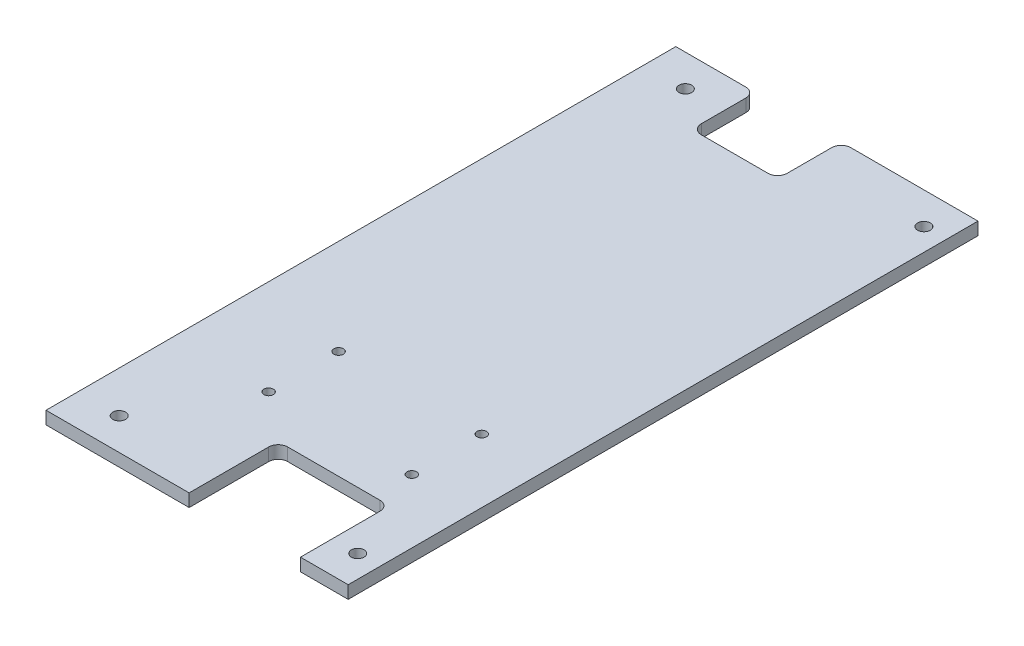
SolidWorks part; units mm, degrees
ref_plane "前视基准面" through (0, 0, 0) normal (0, 0, 1) x (1, 0, 0)
ref_plane "上视基准面" through (0, 0, 0) normal (0, 1, 0) x (1, 0, 0)
ref_plane "右视基准面" through (0, 0, 0) normal (1, 0, 0) x (0, 0, -1)
sketch "草图1" plane through (0, 0, 0) normal (0, 1, 0) x (1, 0, 0)
  line L1 (47.5, -99) -> (-47.5, -99)
  line L2 (47.5, -99) -> (47.5, 99)
  line L3 (47.5, 99) -> (-47.5, 99)
  line L4 (-47.5, -99) -> (-47.5, 99)
  line L5 (47.5, -99) -> (-47.5, 99) construction
  line L6 (47.5, 99) -> (-47.5, -99) construction
  point P0 (0, 0)
  dimension "D1" = 198
  dimension "D2" = 95
extrude "凸台-拉伸1" add sketch "草图1" along normal blind 4
sketch "草图2" plane through (0, 4, 0) normal (0, 1, 0) x (1, 0, 0)
  line L0 (32.5, -99) -> (32.5, -71)
  line L1 (-47.5, -99) -> (47.5, -99) construction
  line L2 (32.5, -71) -> (-2.5, -71)
  line L3 (-2.5, -71) -> (-2.5, -99)
  line L4 (47.5, -99) -> (47.5, 99) construction
  line L5 (-2.5, -99) -> (32.5, -99)
  dimension "D1" = 35
  dimension "D2" = 15
  dimension "D3" = 28
extrude "切除-拉伸1" cut sketch "草图2" against normal blind 4
sketch "草图3" plane through (0, 4, 0) normal (0, 1, 0) x (1, 0, 0)
  line L0 (32.5, -99) -> (32.5, -71) construction
  line L1 (32.5, -99) -> (47.5, -99) construction
  circle A0 centre (40.5, -89) radius 2
  dimension "D1" = 8
  dimension "D2" = 10
  dimension "D3" = 4
extrude "切除-拉伸2" cut sketch "草图3" against normal through all
sketch "草图4" plane through (0, 4, 0) normal (0, 1, 0) x (1, 0, 0)
  line L0 (47.5, 99) -> (-47.5, 99) construction
  line L1 (32.5, -99) -> (32.5, -71) construction
  line L2 (-47.5, -99) -> (-2.5, -99) construction
  circle A0 centre (40.5, 89) radius 2
  circle A1 centre (-34.5, 89) radius 2
  circle A2 centre (-34.5, -89) radius 2
  circle A3 centre (40.5, -89) radius 2 construction
  point P6 (32.5, -85)
  dimension "D1" = 10
  dimension "D2" = 8
  dimension "D3" = 4
  dimension "D4" = 10
  dimension "D5" = 75
  dimension "D6" = 4
  dimension "D7" = 75
  dimension "D8" = 10
  dimension "D9" = 4
extrude "切除-拉伸3" cut sketch "草图4" against normal through all
sketch "草图5" plane through (0, 4, 0) normal (0, 1, 0) x (1, 0, 0)
  line L0 (-22.5, 99) -> (-22.5, 79)
  line L1 (47.5, 99) -> (-47.5, 99) construction
  line L2 (-22.5, 79) -> (4.5, 79)
  line L3 (4.5, 79) -> (4.5, 99)
  line L4 (4.5, 99) -> (-22.5, 99)
  circle A0 centre (-34.5, 89) radius 2 construction
  dimension "D1" = 20
  dimension "D2" = 12
  dimension "D3" = 27
extrude "切除-拉伸4" cut sketch "草图5" against normal through all
sketch "草图6" plane through (0, 4, 0) normal (0, 1, 0) x (1, 0, 0)
  line L0 (-47.5, -99) -> (-2.5, -99) construction
  line L1 (32.5, -99) -> (47.5, -99) construction
  line L4 (47.5, -99) -> (47.5, 99) construction
  circle A0 centre (-17.5, -59) radius 1.5
  circle A1 centre (27.5, -59) radius 1.5
  circle A2 centre (27.5, -37) radius 1.5
  circle A3 centre (-17.5, -37) radius 1.5
  point P12 (40, -99)
  dimension "D1" = 45
  dimension "D2" = 45
  dimension "D3" = 22
  dimension "D4" = 22
  dimension "D5" = 40
  dimension "D6" = 40
  dimension "D7" = 20
  dimension "D8" = 20
  dimension "D9" = 3
  dimension "D10" = 3
  dimension "D11" = 3
  dimension "D12" = 3
extrude "切除-拉伸5" cut sketch "草图6" against normal blind 20
fillet "圆角1" radius 3 2 edges at (32.5, 2, 71) (-2.5, 2, 71)
fillet "圆角2" radius 3 4 edges at (-22.5, 2, -99) (4.5, 2, -99) (-22.5, 2, -79) (4.5, 2, -79)
